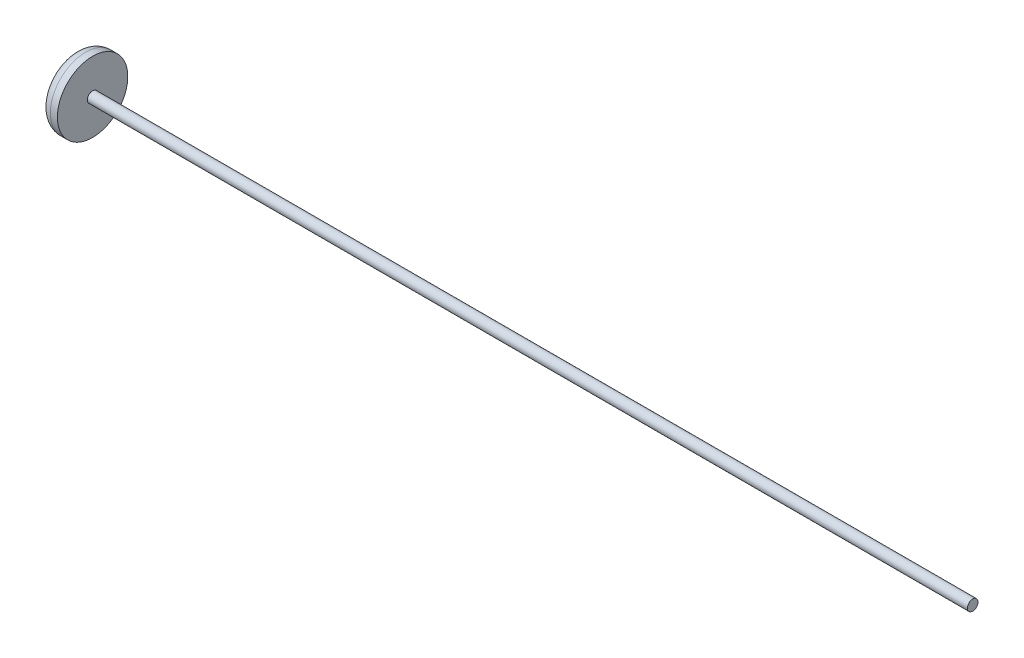
SolidWorks part; units mm, degrees
ref_plane "Front Plane" through (0, 0, 0) normal (0, 0, 1) x (1, 0, 0)
ref_plane "Top Plane" through (0, 0, 0) normal (0, 1, 0) x (1, 0, 0)
ref_plane "Right Plane" through (0, 0, 0) normal (1, 0, 0) x (0, 0, -1)
sketch "Sketch1" plane through (0, 0, 0) normal (1, 0, 0) x (0, 0, -1)
  circle A0 centre (0, 0) radius 0.15
  dimension "D1" = 0.3
extrude "Boss-Extrude1" add sketch "Sketch1" along normal blind 25
sketch "Sketch2" plane through (0, 0, 0) normal (-1, 0, 0) x (0, 0, 1)
  circle A0 centre (0, 0) radius 1
  dimension "D1" = 2
extrude "Boss-Extrude2" add sketch "Sketch2" along normal blind 0.5
fillet "Fillet1" radius 0.3 1 edges at (-0.5, 0, 1)
